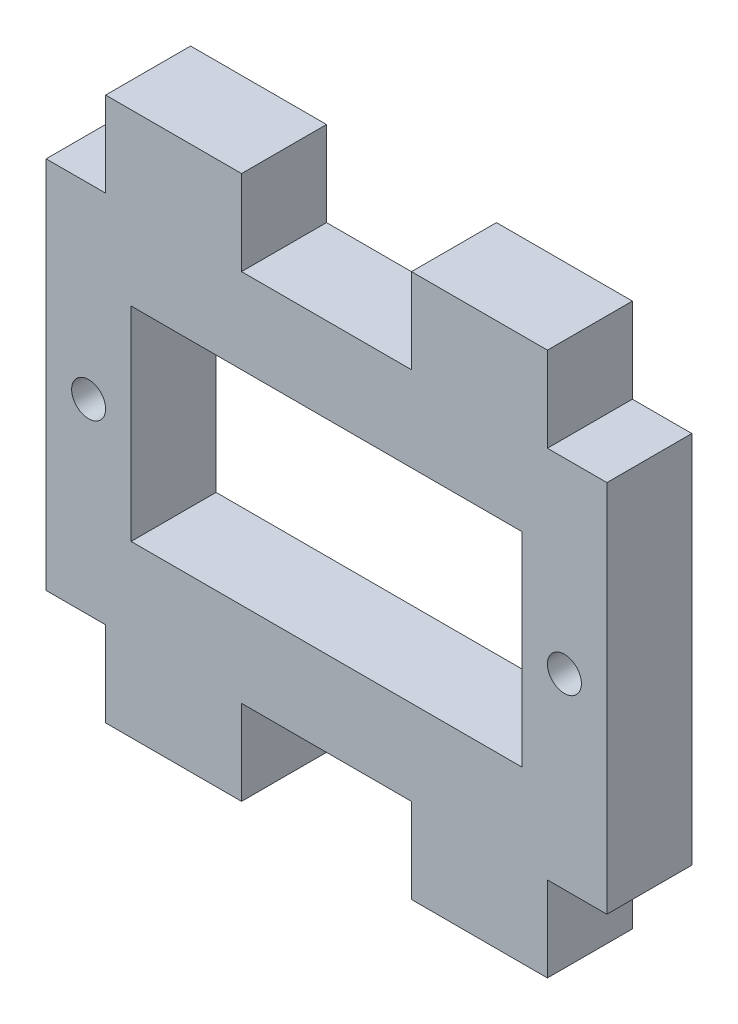
SolidWorks part; units mm, degrees
ref_plane "Plan de face" through (0, 0, 0) normal (0, 0, 1) x (1, 0, 0)
ref_plane "Plan de dessus" through (0, 0, 0) normal (0, 1, 0) x (1, 0, 0)
ref_plane "Plan de droite" through (0, 0, 0) normal (1, 0, 0) x (0, 0, -1)
sketch "Esquisse1" plane through (0, 0, 0) normal (0, 0, 1) x (1, 0, 0)
  line L0 (5, 11) -> (5, 16)
  line L1 (5, 16) -> (13, 16)
  line L2 (13, 16) -> (13, 11)
  line L3 (16.5, 11) -> (13, 11)
  line L4 (16.5, -11) -> (16.5, 11)
  line L5 (13, -11) -> (16.5, -11)
  line L6 (13, -16) -> (13, -11)
  line L7 (5, -16) -> (13, -16)
  line L8 (5, -11) -> (5, -16)
  line L9 (5, -11) -> (-5, -11)
  line L10 (-5, -11) -> (-5, -16)
  line L11 (-13, -16) -> (-5, -16)
  line L12 (-13, -16) -> (-13, -11)
  line L13 (-16.5, -11) -> (-13, -11)
  line L14 (-16.5, 11) -> (-16.5, -11)
  line L15 (-13, 11) -> (-16.5, 11)
  line L16 (-13, 16) -> (-13, 11)
  line L17 (-13, 16) -> (-5, 16)
  line L18 (-5, 11) -> (-5, 16)
  line L19 (5, 11) -> (-5, 11)
  line L20 (-11.5, 6) -> (-11.5, -6)
  line L21 (-11.5, -6) -> (11.5, -6)
  line L22 (11.5, -6) -> (11.5, 6)
  line L23 (11.5, 6) -> (-11.5, 6)
  line L24 (-11.5, 0) -> (11.5, 0) construction
  circle A0 centre (-14, 0) radius 1
  circle A1 centre (14, 0) radius 1
  dimension "D6" = 2
  dimension "D1" = 23
  dimension "D2" = 12
  dimension "D3" = 10
  dimension "D4" = 5
  dimension "D5" = 5
  dimension "D7" = 32
  dimension "D8" = 33
  dimension "D9" = 16.5
  dimension "D10" = 16
  dimension "D11" = 8
  dimension "D12" = 14
  dimension "D13" = 11.5
  dimension "D14" = 14
  dimension "D15" = 5
extrude "Boss.-Extru.1" add sketch "Esquisse1" along normal blind 5
